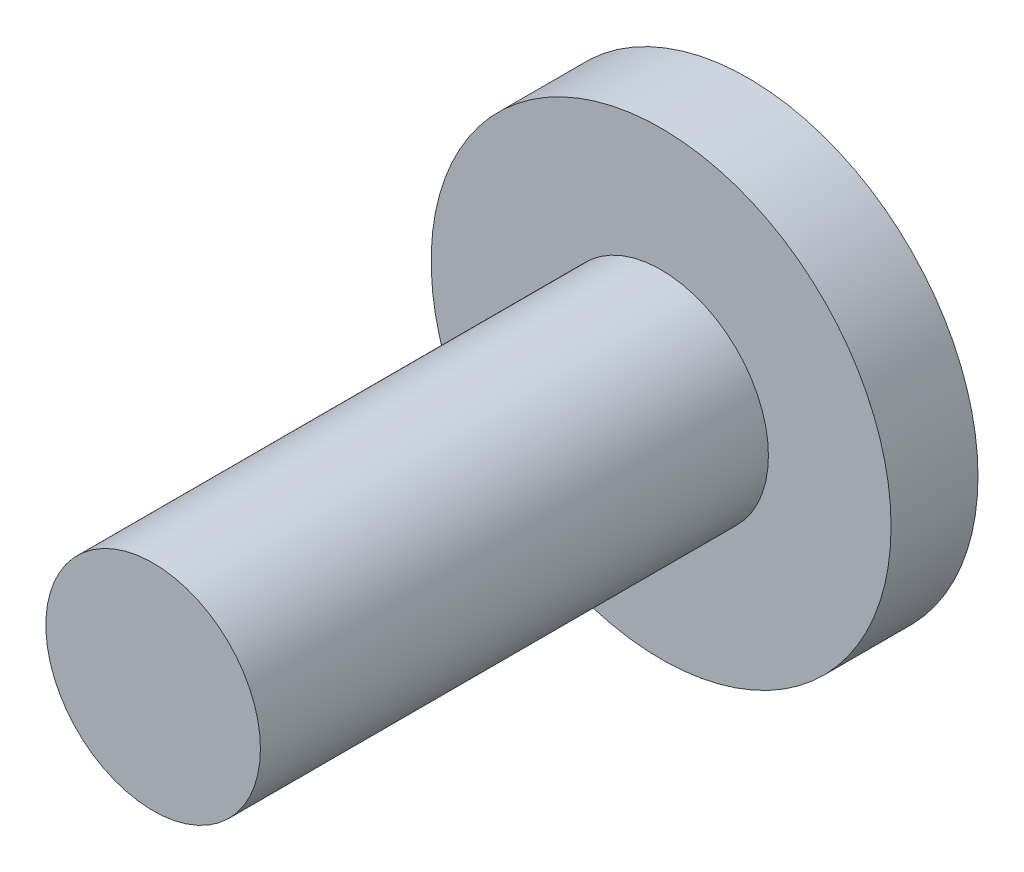
SolidWorks part; units mm, degrees
ref_plane "Front Plane" through (0, 0, 0) normal (0, 0, 1) x (1, 0, 0)
ref_plane "Top Plane" through (0, 0, 0) normal (0, 1, 0) x (1, 0, 0)
ref_plane "Right Plane" through (0, 0, 0) normal (1, 0, 0) x (0, 0, -1)
sketch "Sketch1" plane through (0, 0, 0) normal (0, 0, 1) x (1, 0, 0)
  circle A0 centre (0, 0) radius 8.465
extrude "Head" add sketch "Sketch1" along normal blind 3.2
ref_plane "Plane_z3_2" through (0, 0, 3.2) normal (0, 0, 1) x (1, 0, 0)
sketch "Sketch2" plane through (0, 0, 3.2) normal (0, 0, 1) x (1, 0, 0)
  circle A0 centre (0, 0) radius 3.95
extrude "Shank" add sketch "Sketch2" along normal blind 18.7
